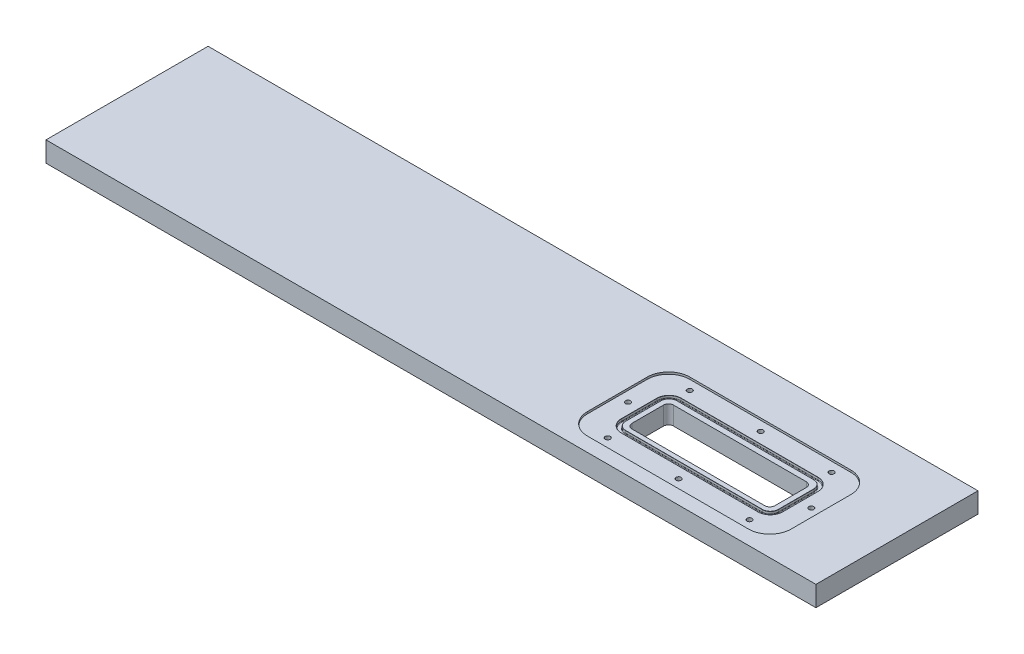
SolidWorks part; units mm, degrees
ref_plane "정면" through (0, 0, 0) normal (0, 0, 1) x (1, 0, 0)
ref_plane "윗면" through (0, 0, 0) normal (0, 1, 0) x (1, 0, 0)
ref_plane "우측면" through (0, 0, 0) normal (1, 0, 0) x (0, 0, -1)
sketch "스케치1" plane through (0, 0, 0) normal (0, 1, 0) x (1, 0, 0)
  line L1 (0, 0) -> (760, 0)
  line L2 (0, 0) -> (0, 160)
  line L3 (0, 160) -> (760, 160)
  line L4 (760, 0) -> (760, 160)
  dimension "D1" = 760
  dimension "D2" = 160
extrude "보스-돌출1" add sketch "스케치1" along normal mid plane 20
sketch "스케치2" plane through (0, 10, 0) normal (0, 1, 0) x (1, 0, 0)
  line L0 (0, 0) -> (760, 0) construction
  line L1 (0, 160) -> (0, 0) construction
  circle A0 centre (280, 80) radius 19
  circle A1 centre (380, 80) radius 19
  dimension "D4" = 38
  dimension "D1" = 80
  dimension "D2" = 280
  dimension "D3" = 100
extrude "컷-돌출1" cut sketch "스케치2" against normal through all
sketch "스케치3" plane through (0, 10, 0) normal (0, 1, 0) x (1, 0, 0)
  line L0 (0, 0) -> (760, 0) construction
  line L1 (520.5, 146) -> (679.5, 146)
  line L2 (499.5, 125) -> (499.5, 66)
  line L3 (520.5, 45) -> (679.5, 45)
  line L4 (700.5, 125) -> (700.5, 66)
  line L5 (760, 0) -> (760, 160) construction
  arc A0 (499.5, 66) -> (520.5, 45) centre (520.5, 66) ccw
  arc A1 (679.5, 146) -> (700.5, 125) centre (679.5, 125) cw
  arc A2 (679.5, 45) -> (700.5, 66) centre (679.5, 66) ccw
  arc A3 (520.5, 146) -> (499.5, 125) centre (520.5, 125) ccw
  point P12 (700.5, 146)
  point P15 (700.5, 45)
  point P18 (499.5, 146)
  dimension "D5" = 21
  dimension "D1" = 45
  dimension "D2" = 101
  dimension "D3" = 201
  dimension "D4" = 59.5
extrude "컷-돌출2" cut sketch "스케치3" against normal blind 2
sketch "스케치4" plane through (0, 8, 0) normal (0, 1, 0) x (1, 0, 0)
  line L0 (760, 0) -> (760, 160) construction
  line L1 (522.5, 122.5) -> (677.5, 122.5) construction
  line L2 (522.5, 122.5) -> (522.5, 67.5) construction
  line L3 (522.5, 67.5) -> (677.5, 67.5) construction
  line L4 (677.5, 122.5) -> (677.5, 67.5) construction
  line L10 (532.5, 124.55) -> (667.5, 124.55)
  line L11 (679.55, 112.5) -> (679.55, 77.5)
  line L12 (532.5, 65.45) -> (667.5, 65.45)
  line L13 (520.45, 112.5) -> (520.45, 77.5)
  line L14 (532.5, 120.45) -> (667.5, 120.45)
  line L15 (675.45, 112.5) -> (675.45, 77.5)
  line L16 (532.5, 69.55) -> (667.5, 69.55)
  line L17 (524.55, 112.5) -> (524.55, 77.5)
  line L18 (520.45, 124.55) -> (679.55, 124.55) construction
  line L19 (520.45, 124.55) -> (520.45, 65.45) construction
  line L20 (520.45, 65.45) -> (679.55, 65.45) construction
  line L21 (679.55, 124.55) -> (679.55, 65.45) construction
  line L22 (524.55, 120.45) -> (675.45, 120.45) construction
  line L23 (675.45, 120.45) -> (675.45, 69.55) construction
  line L24 (524.55, 69.55) -> (675.45, 69.55) construction
  line L25 (524.55, 120.45) -> (524.55, 69.55) construction
  line L26 (0, 0) -> (760, 0) construction
  arc A0 (532.5, 124.55) -> (520.45, 112.5) centre (532.5, 112.5) ccw
  arc A1 (532.5, 65.45) -> (520.45, 77.5) centre (532.5, 77.5) cw
  arc A2 (679.55, 77.5) -> (667.5, 65.45) centre (667.5, 77.5) cw
  arc A3 (667.5, 124.55) -> (679.55, 112.5) centre (667.5, 112.5) cw
  arc A4 (667.5, 120.45) -> (675.45, 112.5) centre (667.5, 112.5) cw
  arc A5 (675.45, 77.5) -> (667.5, 69.55) centre (667.5, 77.5) cw
  arc A6 (532.5, 69.55) -> (524.55, 77.5) centre (532.5, 77.5) cw
  arc A7 (532.5, 120.45) -> (524.55, 112.5) centre (532.5, 112.5) ccw
  dimension "D7" = 12.05
  dimension "D8" = 7.95
  dimension "D1" = 82.5
  dimension "D2" = 55
  dimension "D3" = 67.5
  dimension "D4" = 155
  dimension "D5" = 2.05
  dimension "D6" = 2.05
extrude "컷-돌출4" cut sketch "스케치4" against normal blind 2.7
sketch "스케치5" plane through (0, 8, 0) normal (0, 1, 0) x (1, 0, 0)
  line L0 (0, 0) -> (760, 0) construction
  line L1 (534.5, 116) -> (665.5, 116)
  line L2 (529.5, 111) -> (529.5, 80)
  line L3 (534.5, 75) -> (665.5, 75)
  line L4 (670.5, 111) -> (670.5, 80)
  line L5 (760, 0) -> (760, 160) construction
  arc A0 (529.5, 80) -> (534.5, 75) centre (534.5, 80) ccw
  arc A1 (665.5, 75) -> (670.5, 80) centre (665.5, 80) ccw
  arc A2 (665.5, 116) -> (670.5, 111) centre (665.5, 111) cw
  arc A3 (534.5, 116) -> (529.5, 111) centre (534.5, 111) ccw
  dimension "D5" = 5
  dimension "D1" = 75
  dimension "D2" = 41
  dimension "D3" = 141
  dimension "D4" = 89.5
extrude "컷-돌출5" cut sketch "스케치5" against normal through all
sketch "스케치6" plane through (0, 8, 0) normal (0, 1, 0) x (1, 0, 0)
  line L0 (0, 160) -> (0, 0) construction
  line L1 (0, 0) -> (760, 0) construction
  point P0 (530, 135.5)
  point P1 (600, 135.5)
  point P2 (670, 135.5)
  point P3 (670, 54.5)
  point P4 (600, 54.5)
  point P5 (530, 54.5)
  point P6 (509.5, 95)
  point P7 (690.5, 95)
  dimension "D1" = 20.5
  dimension "D2" = 530
  dimension "D3" = 70
  dimension "D4" = 70
  dimension "D5" = 40.5
  dimension "D6" = 54.5
  dimension "D7" = 40.5
  dimension "D8" = 20.5
hole_wizard "M6 나사 구멍1" positions "스케치6" profile "스케치7" tap size "M6" standard "ISO"
sketch "스케치7" plane through (530, 8, -135.5) normal (1, 0, 0) x (0, 0, 1)
  line L0 (0, 0) -> (0, 16.5022)
  line L1 (0, 16.5022) -> (2.5, 15)
  line L2 (2.5, 15) -> (2.5, 0)
  line L5 (2.5, 0) -> (0, 0)
  line L10 (0, 16.5022) -> (-2.5, 15) construction
  line L11 (0, -6.35) -> (0, 107.95) construction
  dimension "탭 드릴 지름" = 5
  dimension "탭 드릴 깊이" = 15
  dimension "드릴 각도" = 118
cosmetic thread "구멍 나사산1" parameters "D1"=10, "D2"=6
cosmetic thread "구멍 나사산2" parameters "D1"=10, "D2"=6
cosmetic thread "구멍 나사산6" parameters "D1"=10, "D2"=6
cosmetic thread "구멍 나사산7" parameters "D1"=10, "D2"=6
cosmetic thread "구멍 나사산8" parameters "D1"=10, "D2"=6
cosmetic thread "구멍 나사산9" parameters "D1"=10, "D2"=6
cosmetic thread "구멍 나사산10" parameters "D1"=10, "D2"=6
cosmetic thread "구멍 나사산11" parameters "D1"=10, "D2"=6
fillet "필렛1" radius 0.13 8 edges at (676.0206, 8, -121.0206) (679.55, 8, -95) (676.0206, 8, -68.9794) (600, 8, -65.45) (523.9794, 8, -68.9794) (520.45, 8, -95) (523.9794, 8, -121.0206) (600, 8, -124.55)
fillet "필렛2" radius 0.5 8 edges at (600, 5.3, -124.55) (676.0206, 5.3, -121.0206) (679.55, 5.3, -95) (676.0206, 5.3, -68.9794) (600, 5.3, -65.45) (523.9794, 5.3, -68.9794) (520.45, 5.3, -95) (523.9794, 5.3, -121.0206)
fillet "필렛3" radius 0.5 8 edges at (526.8785, 5.3, -118.1215) (600, 5.3, -120.45) (673.1215, 5.3, -118.1215) (675.45, 5.3, -95) (673.1215, 5.3, -71.8785) (600, 5.3, -69.55) (526.8785, 5.3, -71.8785) (524.55, 5.3, -95)
fillet "필렛4" radius 0.13 8 edges at (526.8785, 8, -118.1215) (600, 8, -120.45) (673.1215, 8, -118.1215) (675.45, 8, -95) (673.1215, 8, -71.8785) (600, 8, -69.55) (526.8785, 8, -71.8785) (524.55, 8, -95)
sketch "스케치8" plane through (0, 10, 0) normal (0, 1, 0) x (1, 0, 0)
  line L1 (218.6257, 132.282) -> (430.2236, 132.282)
  line L2 (218.6257, 132.282) -> (218.6257, 27.718)
  line L3 (218.6257, 27.718) -> (430.2236, 27.718)
  line L4 (430.2236, 132.282) -> (430.2236, 27.718)
extrude "보스-돌출3" add sketch "스케치8" against normal up to surface (20 mm away) up to face at (600, -10, -95.5)
ref_plane "평면1" through (0, 0, 0) normal (0, 0, 1) x (1, 0, 0)
mirror "대칭 복사2" of "보스-돌출3", "필렛4", "필렛3", "필렛2", "필렛1", "M6 나사 구멍1", "컷-돌출5", "컷-돌출4", "컷-돌출2", "컷-돌출1", "보스-돌출1"
cosmetic thread "구멍 나사산12" parameters "D1"=10, "D2"=6
cosmetic thread "구멍 나사산13" parameters "D1"=10, "D2"=6
cosmetic thread "구멍 나사산14" parameters "D1"=10, "D2"=6
cosmetic thread "구멍 나사산15" parameters "D1"=10, "D2"=6
cosmetic thread "구멍 나사산16" parameters "D1"=10, "D2"=6
cosmetic thread "구멍 나사산17" parameters "D1"=10, "D2"=6
cosmetic thread "구멍 나사산18" parameters "D1"=10, "D2"=6
cosmetic thread "구멍 나사산19" parameters "D1"=10, "D2"=6
sketch "스케치9" plane through (0, 0, 0) normal (0, 0, 1) x (1, 0, 0)
  line L1 (-16.5955, 48.9782) -> (807.9789, 48.9782)
  line L2 (-16.5955, 48.9782) -> (-16.5955, -77.2798)
  line L3 (-16.5955, -77.2798) -> (807.9789, -77.2798)
  line L4 (807.9789, 48.9782) -> (807.9789, -77.2798)
extrude "컷-돌출6" cut sketch "스케치9" against normal through all
